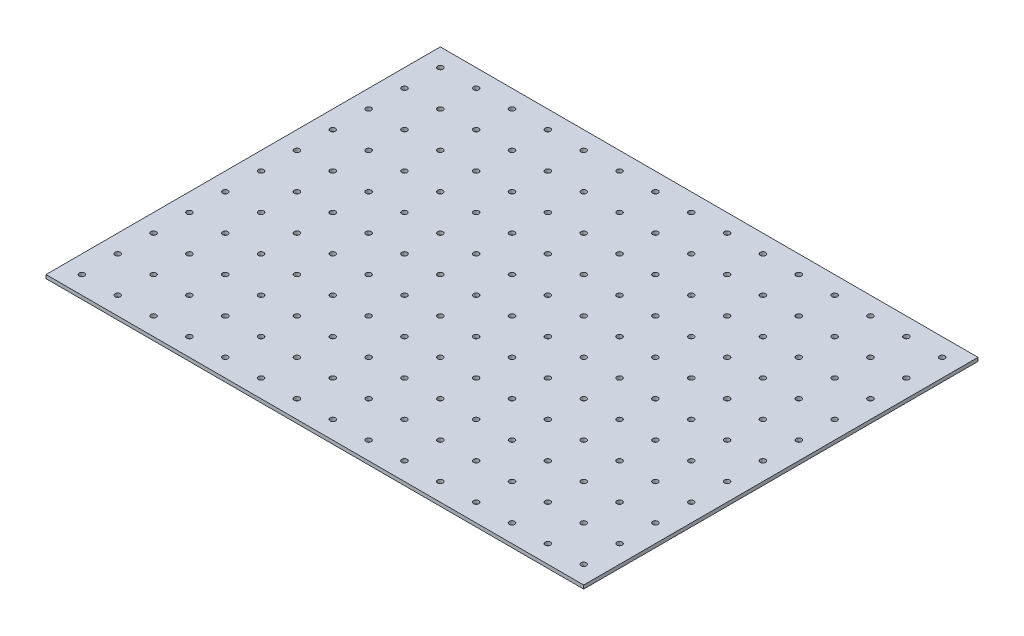
SolidWorks part; units mm, degrees
ref_plane "Front Plane" through (0, 0, 0) normal (0, 0, 1) x (1, 0, 0)
ref_plane "Top Plane" through (0, 0, 0) normal (0, 1, 0) x (1, 0, 0)
ref_plane "Right Plane" through (0, 0, 0) normal (1, 0, 0) x (0, 0, -1)
sketch "Sketch1" plane through (0, 0, 0) normal (0, 0, 1) x (1, 0, 0)
  line L1 (-150, 1) -> (150, 1)
  line L2 (-150, 1) -> (-150, -1)
  line L3 (-150, -1) -> (150, -1)
  line L4 (150, 1) -> (150, -1)
  line L5 (-150, 1) -> (150, -1) construction
  line L6 (-150, -1) -> (150, 1) construction
  point P0 (0, 0)
  dimension "D1" = 2
  dimension "D2" = 300
extrude "Boss-Extrude1" add sketch "Sketch1" along normal mid plane 220
sketch "Sketch2" plane through (0, 1, 0) normal (0, 1, 0) x (1, 0, 0)
  line L0 (-150, -110) -> (-150, 110) construction
  line L1 (150, -110) -> (-150, -110) construction
  circle A0 centre (-140, -100) radius 1.5
  circle A1 centre (-120, -100) radius 1.5
  circle A2 centre (-100, -100) radius 1.5
  circle A3 centre (-80, -100) radius 1.5
  circle A4 centre (-60, -100) radius 1.5
  circle A5 centre (-40, -100) radius 1.5
  circle A6 centre (-20, -100) radius 1.5
  circle A7 centre (0, -100) radius 1.5
  circle A8 centre (20, -100) radius 1.5
  circle A9 centre (40, -100) radius 1.5
  circle A10 centre (60, -100) radius 1.5
  circle A11 centre (80, -100) radius 1.5
  circle A12 centre (100, -100) radius 1.5
  circle A13 centre (120, -100) radius 1.5
  circle A14 centre (140, -100) radius 1.5
  circle A15 centre (-120, -80) radius 1.5
  circle A16 centre (-100, -80) radius 1.5
  circle A17 centre (-80, -80) radius 1.5
  circle A18 centre (-60, -80) radius 1.5
  circle A19 centre (-40, -80) radius 1.5
  circle A20 centre (-20, -80) radius 1.5
  circle A21 centre (0, -80) radius 1.5
  circle A22 centre (20, -80) radius 1.5
  circle A23 centre (40, -80) radius 1.5
  circle A24 centre (60, -80) radius 1.5
  circle A25 centre (80, -80) radius 1.5
  circle A26 centre (100, -80) radius 1.5
  circle A27 centre (120, -80) radius 1.5
  circle A28 centre (140, -80) radius 1.5
  circle A29 centre (-120, -60) radius 1.5
  circle A30 centre (-100, -60) radius 1.5
  circle A31 centre (-80, -60) radius 1.5
  circle A32 centre (-60, -60) radius 1.5
  circle A33 centre (-40, -60) radius 1.5
  circle A34 centre (-20, -60) radius 1.5
  circle A35 centre (0, -60) radius 1.5
  circle A36 centre (20, -60) radius 1.5
  circle A37 centre (40, -60) radius 1.5
  circle A38 centre (60, -60) radius 1.5
  circle A39 centre (80, -60) radius 1.5
  circle A40 centre (100, -60) radius 1.5
  circle A41 centre (120, -60) radius 1.5
  circle A42 centre (140, -60) radius 1.5
  circle A43 centre (-120, -40) radius 1.5
  circle A44 centre (-100, -40) radius 1.5
  circle A45 centre (-80, -40) radius 1.5
  circle A46 centre (-60, -40) radius 1.5
  circle A47 centre (-40, -40) radius 1.5
  circle A48 centre (-20, -40) radius 1.5
  circle A49 centre (0, -40) radius 1.5
  circle A50 centre (20, -40) radius 1.5
  circle A51 centre (40, -40) radius 1.5
  circle A52 centre (60, -40) radius 1.5
  circle A53 centre (80, -40) radius 1.5
  circle A54 centre (100, -40) radius 1.5
  circle A55 centre (120, -40) radius 1.5
  circle A56 centre (140, -40) radius 1.5
  circle A57 centre (-120, -20) radius 1.5
  circle A58 centre (-100, -20) radius 1.5
  circle A59 centre (-80, -20) radius 1.5
  circle A60 centre (-60, -20) radius 1.5
  circle A61 centre (-40, -20) radius 1.5
  circle A62 centre (-20, -20) radius 1.5
  circle A63 centre (0, -20) radius 1.5
  circle A64 centre (20, -20) radius 1.5
  circle A65 centre (40, -20) radius 1.5
  circle A66 centre (60, -20) radius 1.5
  circle A67 centre (80, -20) radius 1.5
  circle A68 centre (100, -20) radius 1.5
  circle A69 centre (120, -20) radius 1.5
  circle A70 centre (140, -20) radius 1.5
  circle A71 centre (-120, 0) radius 1.5
  circle A72 centre (-100, 0) radius 1.5
  circle A73 centre (-80, 0) radius 1.5
  circle A74 centre (-60, 0) radius 1.5
  circle A75 centre (-40, 0) radius 1.5
  circle A76 centre (-20, 0) radius 1.5
  circle A77 centre (0, 0) radius 1.5
  circle A78 centre (20, 0) radius 1.5
  circle A79 centre (40, 0) radius 1.5
  circle A80 centre (60, 0) radius 1.5
  circle A81 centre (80, 0) radius 1.5
  circle A82 centre (100, 0) radius 1.5
  circle A83 centre (120, 0) radius 1.5
  circle A84 centre (140, 0) radius 1.5
  circle A85 centre (-120, 20) radius 1.5
  circle A86 centre (-100, 20) radius 1.5
  circle A87 centre (-80, 20) radius 1.5
  circle A88 centre (-60, 20) radius 1.5
  circle A89 centre (-40, 20) radius 1.5
  circle A90 centre (-20, 20) radius 1.5
  circle A91 centre (0, 20) radius 1.5
  circle A92 centre (20, 20) radius 1.5
  circle A93 centre (40, 20) radius 1.5
  circle A94 centre (60, 20) radius 1.5
  circle A95 centre (80, 20) radius 1.5
  circle A96 centre (100, 20) radius 1.5
  circle A97 centre (120, 20) radius 1.5
  circle A98 centre (140, 20) radius 1.5
  circle A99 centre (-120, 40) radius 1.5
  circle A100 centre (-100, 40) radius 1.5
  circle A101 centre (-80, 40) radius 1.5
  circle A102 centre (-60, 40) radius 1.5
  circle A103 centre (-40, 40) radius 1.5
  circle A104 centre (-20, 40) radius 1.5
  circle A105 centre (0, 40) radius 1.5
  circle A106 centre (20, 40) radius 1.5
  circle A107 centre (40, 40) radius 1.5
  circle A108 centre (60, 40) radius 1.5
  circle A109 centre (80, 40) radius 1.5
  circle A110 centre (100, 40) radius 1.5
  circle A111 centre (120, 40) radius 1.5
  circle A112 centre (140, 40) radius 1.5
  circle A113 centre (-120, 60) radius 1.5
  circle A114 centre (-100, 60) radius 1.5
  circle A115 centre (-80, 60) radius 1.5
  circle A116 centre (-60, 60) radius 1.5
  circle A117 centre (-40, 60) radius 1.5
  circle A118 centre (-20, 60) radius 1.5
  circle A119 centre (0, 60) radius 1.5
  circle A120 centre (20, 60) radius 1.5
  circle A121 centre (40, 60) radius 1.5
  circle A122 centre (60, 60) radius 1.5
  circle A123 centre (80, 60) radius 1.5
  circle A124 centre (100, 60) radius 1.5
  circle A125 centre (120, 60) radius 1.5
  circle A126 centre (140, 60) radius 1.5
  circle A127 centre (-120, 80) radius 1.5
  circle A128 centre (-100, 80) radius 1.5
  circle A129 centre (-80, 80) radius 1.5
  circle A130 centre (-60, 80) radius 1.5
  circle A131 centre (-40, 80) radius 1.5
  circle A132 centre (-20, 80) radius 1.5
  circle A133 centre (0, 80) radius 1.5
  circle A134 centre (20, 80) radius 1.5
  circle A135 centre (40, 80) radius 1.5
  circle A136 centre (60, 80) radius 1.5
  circle A137 centre (80, 80) radius 1.5
  circle A138 centre (100, 80) radius 1.5
  circle A139 centre (120, 80) radius 1.5
  circle A140 centre (140, 80) radius 1.5
  circle A141 centre (-120, 100) radius 1.5
  circle A142 centre (-100, 100) radius 1.5
  circle A143 centre (-80, 100) radius 1.5
  circle A144 centre (-60, 100) radius 1.5
  circle A145 centre (-40, 100) radius 1.5
  circle A146 centre (-20, 100) radius 1.5
  circle A147 centre (0, 100) radius 1.5
  circle A148 centre (20, 100) radius 1.5
  circle A149 centre (40, 100) radius 1.5
  circle A150 centre (60, 100) radius 1.5
  circle A151 centre (80, 100) radius 1.5
  circle A152 centre (100, 100) radius 1.5
  circle A153 centre (120, 100) radius 1.5
  circle A154 centre (140, 100) radius 1.5
  circle A155 centre (-140, -80) radius 1.5
  circle A156 centre (-140, -60) radius 1.5
  circle A157 centre (-140, -40) radius 1.5
  circle A158 centre (-140, -20) radius 1.5
  circle A159 centre (-140, 0) radius 1.5
  circle A160 centre (-140, 20) radius 1.5
  circle A161 centre (-140, 40) radius 1.5
  circle A162 centre (-140, 60) radius 1.5
  circle A163 centre (-140, 80) radius 1.5
  circle A164 centre (-140, 100) radius 1.5
  dimension "D1" = 3
  dimension "D2" = 10
  dimension "D3" = 10
  dimension "D4" = 15
  dimension "D5" = 11
extrude "Cut-Extrude1" cut sketch "Sketch2" against normal up to next (2 mm away)
